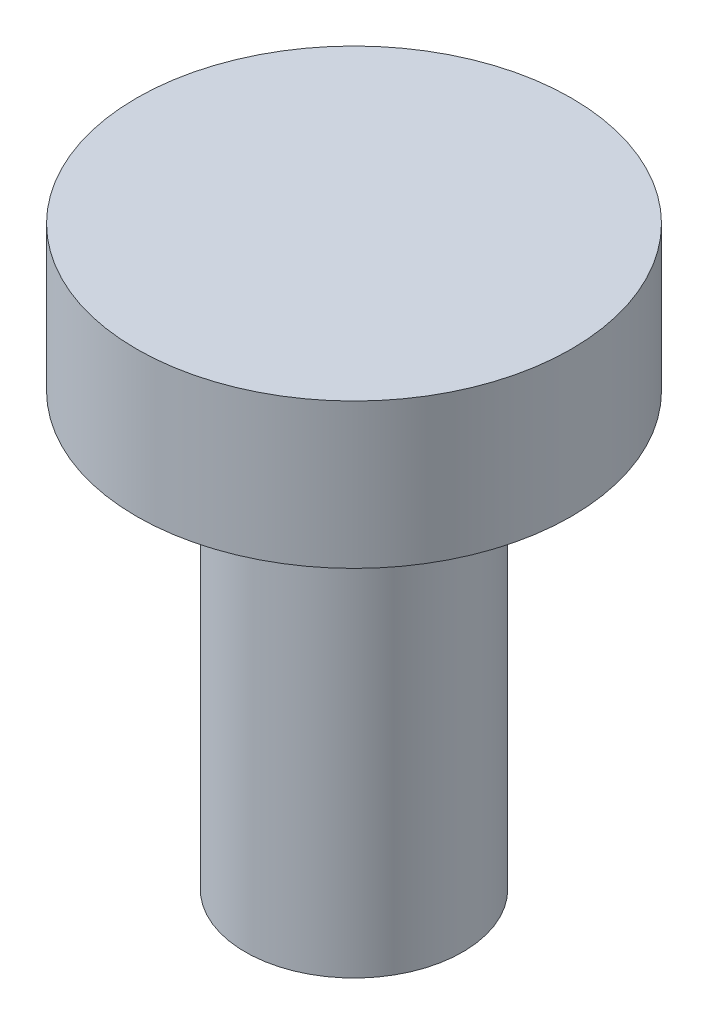
SolidWorks part; units mm, degrees
ref_plane "Спереди" through (0, 0, 0) normal (0, 0, 1) x (1, 0, 0)
ref_plane "Сверху" through (0, 0, 0) normal (0, 1, 0) x (1, 0, 0)
ref_plane "Справа" through (0, 0, 0) normal (1, 0, 0) x (0, 0, -1)
other "Configuration Table"
sketch "Sketch1" plane through (0, 0, 0) normal (0, 0, 1) x (1, 0, 0)
  line L1 (0, 0) -> (1.5, 0)
  line L2 (0, 0) -> (0, 5.9555)
  line L3 (0, 5.9555) -> (1.5, 5.9555)
  line L4 (1.5, 0) -> (1.5, 5.9555)
  line L5 (0, 5.9555) -> (3, 5.9555)
  line L6 (0, 5.9555) -> (0, 7.9555)
  line L7 (0, 7.9555) -> (3, 7.9555)
  line L8 (3, 5.9555) -> (3, 7.9555)
  dimension "D1" = 2
  dimension "D2" = 3
  dimension "D3" = 1.5
revolve "Revolve1" add sketch "Sketch1" angle 360 about L6
